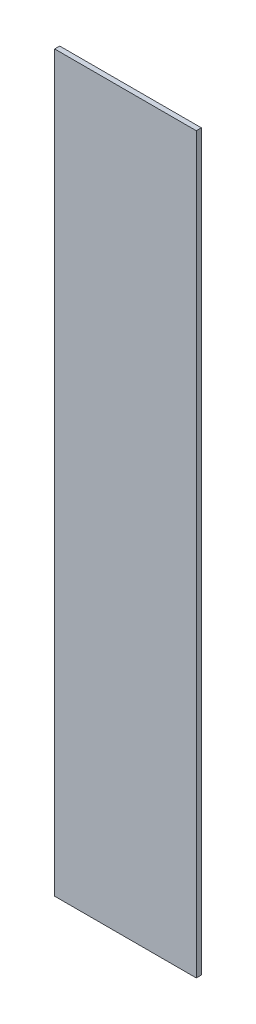
SolidWorks part; units mm, degrees
material "Oak"
ref_plane "Front Plane" through (0, 0, 0) normal (0, 0, 1) x (1, 0, 0)
ref_plane "Top Plane" through (0, 0, 0) normal (0, 1, 0) x (1, 0, 0)
ref_plane "Right Plane" through (0, 0, 0) normal (1, 0, 0) x (0, 0, -1)
sketch "Sketch1" plane through (0, 0, 0) normal (0, 0, 1) x (1, 0, 0)
  line L1 (-88.9, -460.375) -> (88.9, -460.375)
  line L2 (-88.9, -460.375) -> (-88.9, 460.375)
  line L3 (-88.9, 460.375) -> (88.9, 460.375)
  line L4 (88.9, -460.375) -> (88.9, 460.375)
  line L5 (-88.9, -460.375) -> (88.9, 460.375) construction
  line L6 (-88.9, 460.375) -> (88.9, -460.375) construction
  point P0 (0, 0)
  dimension "D1" = 920.75
  dimension "D2" = 177.8
extrude "Boss-Extrude1" add sketch "Sketch1" along normal blind 6.35
